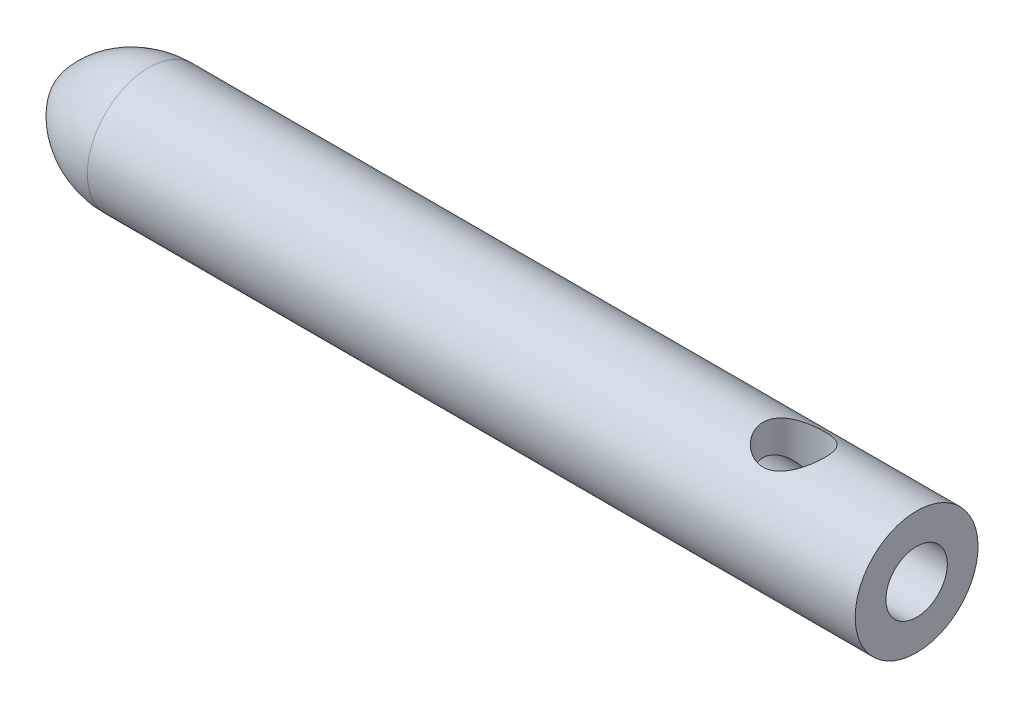
SolidWorks part; units mm, degrees
ref_plane "Front Plane" through (0, 0, 0) normal (0, 0, 1) x (1, 0, 0)
ref_plane "Top Plane" through (0, 0, 0) normal (0, 1, 0) x (1, 0, 0)
ref_plane "Right Plane" through (0, 0, 0) normal (1, 0, 0) x (0, 0, -1)
sketch "Sketch1" plane through (0, 0, 0) normal (0, 0, 1) x (1, 0, 0)
  line L0 (0, 0.8346) -> (25, 0.8346)
  line L1 (-3, -1.1654) -> (25, -1.1654)
  line L2 (25, 0.8346) -> (25, -1.1654)
  arc A1 (0, 0.8346) -> (-3, -1.1654) centre (0, -2.4154) ccw
  dimension "D1" = 25
  dimension "D2" = 2
  dimension "D3" = 3
revolve "Revolve1" add sketch "Sketch1" angle 360 about L1
ref_plane "Plane1" through (0, 0.8346, 0) normal (0, 1, 0) x (1, 0, 0)
sketch "Sketch4" plane through (0, 0.8346, 0) normal (0, 1, 0) x (1, 0, 0)
  line L0 (25, -2) -> (25, 2) construction
  circle A0 centre (21, 0) radius 1
  dimension "D2" = 2
  dimension "D1" = 4
extrude "Cut-Extrude1" cut sketch "Sketch4" against normal blind 2
sketch "Sketch5" plane through (25, 0, 0) normal (1, 0, 0) x (0, 0, -1)
  circle A0 centre (0, -1.1654) radius 1
  dimension "D2" = 2
extrude "Cut-Extrude2" cut sketch "Sketch5" against normal blind 10
